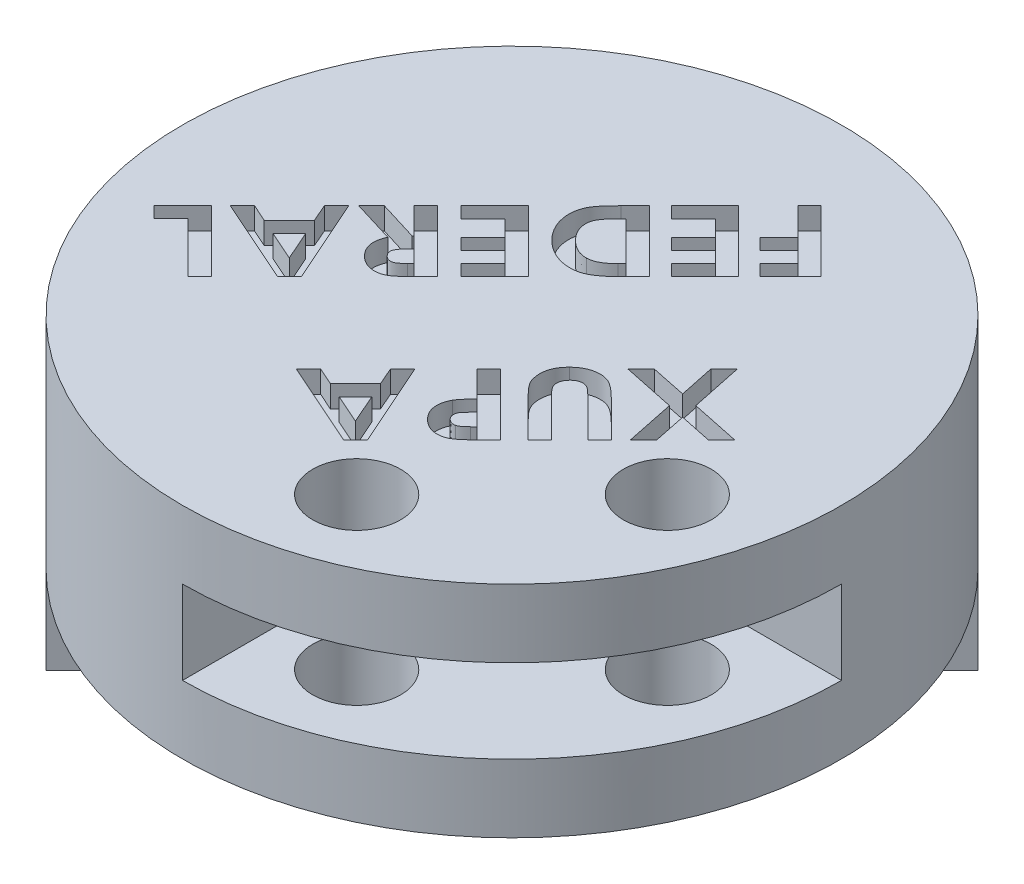
SolidWorks part; units mm, degrees
ref_plane "Plano frontal" through (0, 0, 0) normal (0, 0, 1) x (1, 0, 0)
ref_plane "Plano superior" through (0, 0, 0) normal (0, 1, 0) x (1, 0, 0)
ref_plane "Plano direito" through (0, 0, 0) normal (1, 0, 0) x (0, 0, -1)
sketch "Esboço1" plane through (0, 0, 0) normal (0, 1, 0) x (1, 0, 0)
  circle A0 centre (0, 0) radius 15
  dimension "D1" = 30
extrude "Ressalto-extrusão1" add sketch "Esboço1" along normal blind 10
ref_plane "Plano1" through (0, 5, 0) normal (0, 1, 0) x (1, 0, 0)
sketch "Esboço2" plane through (0, 5, 0) normal (0, 1, 0) x (1, 0, 0)
  line L0 (0, 0) -> (0, -15)
  line L1 (0, 0) -> (15, 0)
  arc A0 (0, -15) -> (15, 0) centre (0, 0) ccw
extrude "Corte-extrusão1" cut sketch "Esboço2" against normal mid plane 3.8
sketch "Esboço3" plane through (0, 10, 0) normal (0, 1, 0) x (1, 0, 0)
  line L0 (10.6066, 10.6066) -> (-10.6066, -10.6066) construction
  line L1 (12.5741, 8.3315) -> (-9.2306, -13.4732) construction
  line L2 (0, 0) -> (-15, 0) construction
  circle A0 centre (0, 0) radius 15 construction
  text T0 "<b>XUPA </b>\r\n<b>FEDERAL</b>" font "Century Gothic" height 4
  point P7 (0, 0)
  point P11 (1.6718, -2.5709)
  dimension "D1" = 3
  dimension "D2" = 45
extrude "Corte-extrusão2" cut sketch "Esboço3" against normal blind 1
sketch "Esboço4" plane through (0, 10, 0) normal (0, 1, 0) x (1, 0, 0)
  line L0 (0, 0) -> (7.0711, -7.0711) construction
  line L1 (0, 0) -> (13.048, 0) construction
  line L2 (10.6066, -3.5355) -> (3.5355, -10.6066) construction
  circle A1 centre (10.6066, -3.5355) radius 2
  circle A2 centre (3.5355, -10.6066) radius 2
  point P8 (7.0711, -7.0711)
  dimension "D2" = 4
  dimension "D1" = 45
  dimension "D3" = 10
  dimension "D4" = 10
extrude "Corte-extrusão3" cut sketch "Esboço4" against normal blind 10
sketch "Esboço5" plane through (0, 0, 0) normal (0, -1, 0) x (1, 0, 0)
  line L2 (-10.6066, 10.6066) -> (10.6066, -10.6066)
  line L3 (0, 0) -> (0, 15) construction
  arc A0 (-10.6066, 10.6066) -> (10.6066, -10.6066) centre (0, 0) ccw
  point P7 (0, 0)
  dimension "D1" = 45
extrude "Ressalto-extrusão2" add sketch "Esboço5" along normal blind 4
